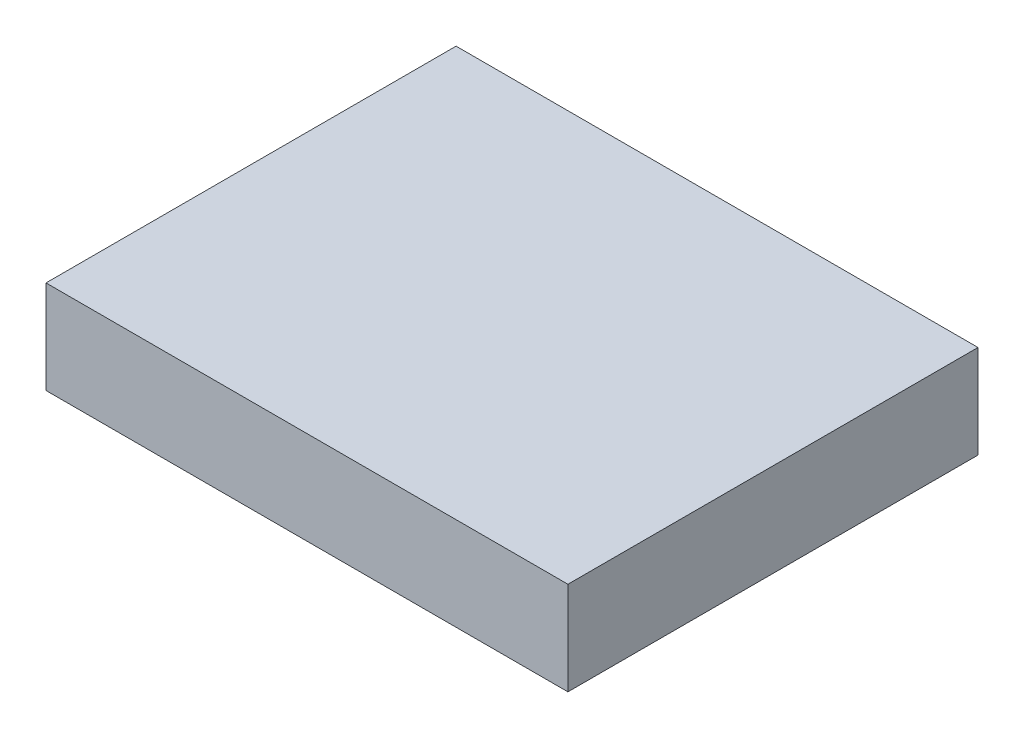
SolidWorks part; units mm, degrees
ref_plane "Front" through (0, 0, 0) normal (0, 0, 1) x (1, 0, 0)
ref_plane "Top" through (0, 0, 0) normal (0, 1, 0) x (1, 0, 0)
ref_plane "Right" through (0, 0, 0) normal (1, 0, 0) x (0, 0, -1)
sketch "Sketch2" plane through (0, 0, 0) normal (0, 1, 0) x (1, 0, 0)
  line L1 (-355.6, -279.4) -> (355.6, -279.4)
  line L2 (-355.6, -279.4) -> (-355.6, 279.4)
  line L3 (-355.6, 279.4) -> (355.6, 279.4)
  line L4 (355.6, -279.4) -> (355.6, 279.4)
  line L5 (-355.6, -279.4) -> (355.6, 279.4) construction
  line L6 (-355.6, 279.4) -> (355.6, -279.4) construction
  point P0 (0, 0)
extrude "Boss-Extrude1" add sketch "Sketch2" along normal blind 127
